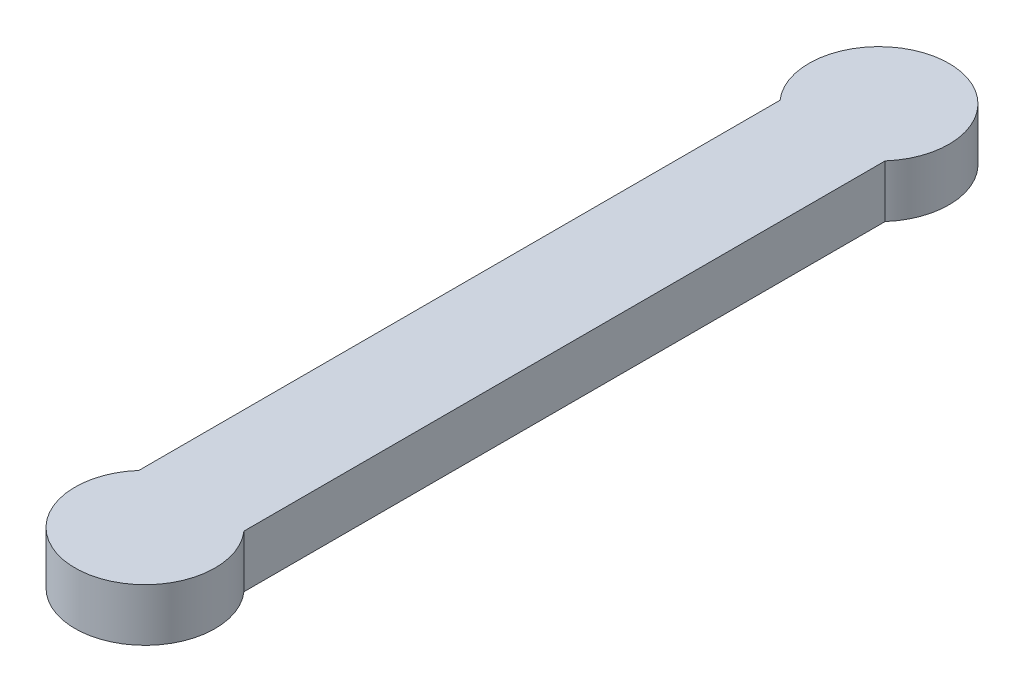
SolidWorks part; units mm, degrees
ref_plane "Front Plane" through (0, 0, 0) normal (0, 0, 1) x (1, 0, 0)
ref_plane "Top Plane" through (0, 0, 0) normal (0, 1, 0) x (1, 0, 0)
ref_plane "Right Plane" through (0, 0, 0) normal (1, 0, 0) x (0, 0, -1)
sketch "Sketch1" plane through (0, 0, 0) normal (0, 1, 0) x (1, 0, 0)
  line L0 (0, 0) -> (0, 51.8396) construction
  line L1 (-3, 39.2542) -> (-3, 2.6458)
  line L2 (3, 39.2542) -> (3, 2.6458)
  arc A0 (-3, 2.6458) -> (3, 2.6458) centre (0, 0) ccw
  arc A1 (3, 39.2542) -> (-3, 39.2542) centre (0, 41.9) ccw
  point P8 (-1.6854, 41.2164)
  point P9 (0, 0)
  dimension "D2" = 8
  dimension "D3" = 8
  dimension "D1" = 41.9
  dimension "D4" = 3
extrude "Boss-Extrude1" add sketch "Sketch1" along normal blind 3
